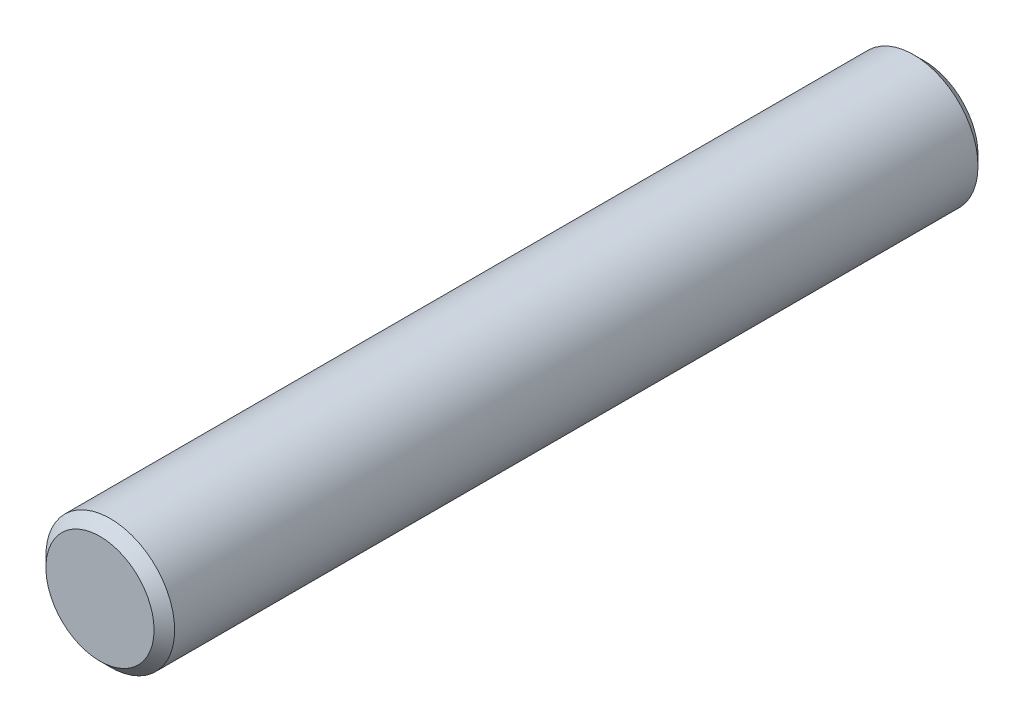
SolidWorks part; units mm, degrees
material "AISI 316 Stainless Steel Sheet (SS)"
ref_plane "Front Plane" through (0, 0, 0) normal (0, 0, 1) x (1, 0, 0)
ref_plane "Top Plane" through (0, 0, 0) normal (0, 1, 0) x (1, 0, 0)
ref_plane "Right Plane" through (0, 0, 0) normal (1, 0, 0) x (0, 0, -1)
sketch "Sketch1" plane through (0, 0, 0) normal (0, 0, 1) x (1, 0, 0)
  circle A0 centre (0, 0) radius 6.35
  dimension "D1" = 12.7
extrude "Boss-Extrude1" add sketch "Sketch1" along normal blind 81.28
chamfer "Chamfer1" distance 1.016 angle 45 2 edges at (6.35, 0, 0) (6.35, 0, 81.28)
